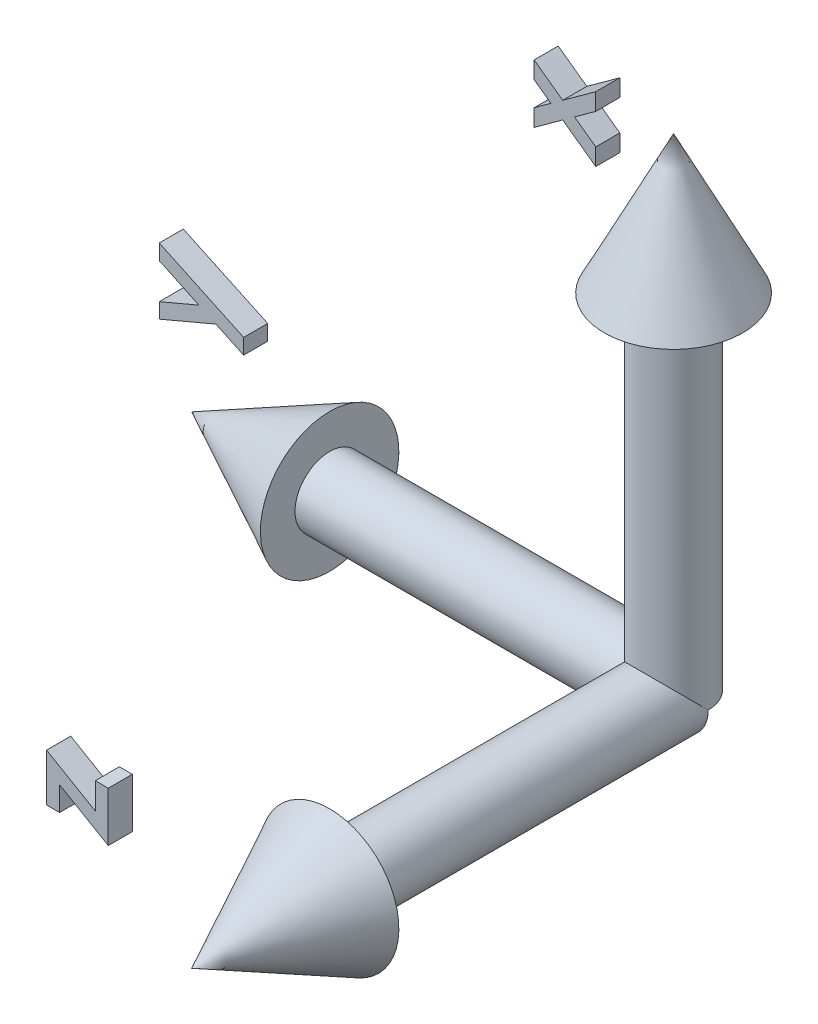
SolidWorks part; units mm, degrees
ref_plane "Front Plane" through (0, 0, 0) normal (0, 0, 1) x (1, 0, 0)
ref_plane "Top Plane" through (0, 0, 0) normal (0, 1, 0) x (1, 0, 0)
ref_plane "Right Plane" through (0, 0, 0) normal (1, 0, 0) x (0, 0, -1)
sketch "Sketch1" plane through (0, 0, 0) normal (0, 0, 1) x (1, 0, 0)
  line L0 (0, 0) -> (0, 20)
  line L1 (0, 20) -> (2.8734, 14.2742)
  line L2 (2.8734, 14.2742) -> (1.4367, 14.2742)
  line L3 (1.4367, 14.2742) -> (1.4367, 0)
  line L4 (1.4367, 0) -> (0, 0)
revolve "Revolve1" add sketch "Sketch1" angle 360 about L0
sketch "Sketch3" plane through (0, 0, 0) normal (0, 0, 1) x (1, 0, 0)
  line L0 (0, 0) -> (-20, 0)
  line L1 (-20, 0) -> (-14.2742, 2.8734)
  line L2 (-14.2742, 2.8734) -> (-14.2742, 1.4367)
  line L3 (-14.2742, 1.4367) -> (0, 1.4367)
  line L4 (0, 1.4367) -> (0, 0)
revolve "Revolve2" add sketch "Sketch3" angle 360 about L0
sketch "Sketch5" plane through (0, 0, 0) normal (1, 0, 0) x (0, 0, -1)
  line L0 (0, 0) -> (-20, 0)
  line L1 (-20, 0) -> (-14.2742, 2.8734)
  line L2 (-14.2742, 2.8734) -> (-14.2742, 1.4367)
  line L3 (-14.2742, 1.4367) -> (0, 1.4367)
  line L4 (0, 1.4367) -> (0, 0)
revolve "Revolve3" add sketch "Sketch5" angle 360 about L0
sketch "Sketch2" plane through (0, 0, 0) normal (0, 0, 1) x (1, 0, 0)
  text T0 "<b><r90>x</r></b>" font "Century Gothic" height 3.5
  text T1 "<b><r90>y</r></b>"
extrude "Boss-Extrude2" add sketch "Sketch2" along normal mid plane 1 separate body
sketch "Sketch7" plane through (0, 0, 0) normal (0, 0, 1) x (1, 0, 0)
  text T0 "<b><r90>z</r></b>"
extrude "Boss-Extrude3" add sketch "Sketch7" along normal mid plane 1 from offset 20 separate body
